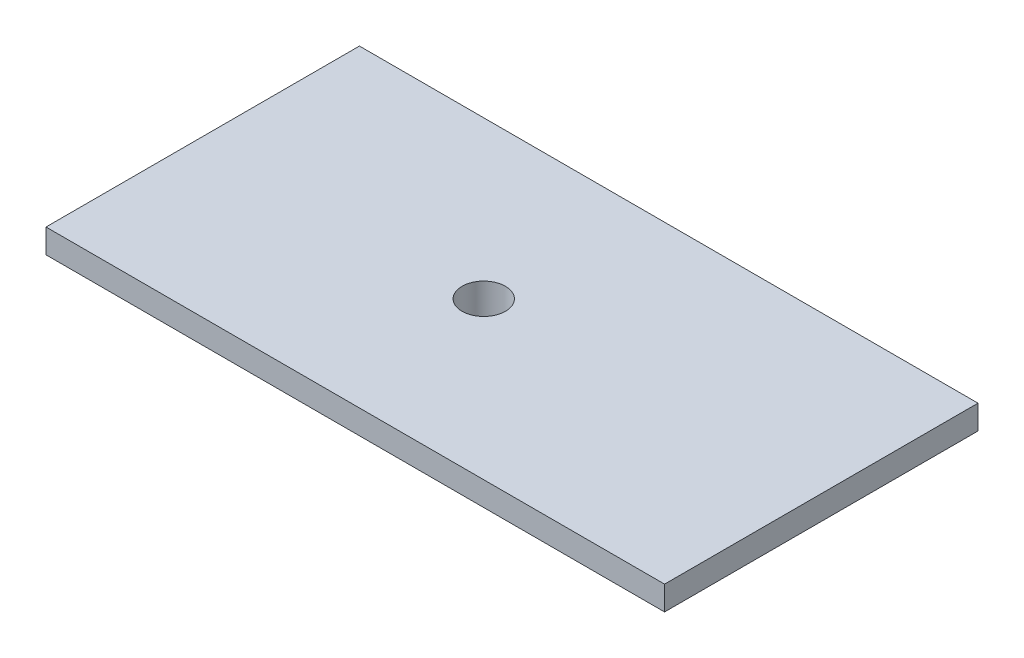
SolidWorks part; units mm, degrees
material "Pure Gold"
ref_plane "Front Plane" through (0, 0, 0) normal (0, 0, 1) x (1, 0, 0)
ref_plane "Top Plane" through (0, 0, 0) normal (0, 1, 0) x (1, 0, 0)
ref_plane "Right Plane" through (0, 0, 0) normal (1, 0, 0) x (0, 0, -1)
sketch "Sketch1" plane through (0, 0, 0) normal (0, 1, 0) x (1, 0, 0)
  line L1 (0, 0) -> (-128.28, 0)
  line L2 (0, 0) -> (0, 65)
  line L3 (0, 65) -> (-128.28, 65)
  line L4 (-128.28, 0) -> (-128.28, 65)
  dimension "D1" = 128.28
  dimension "D2" = 65
extrude "Boss-Extrude1" add sketch "Sketch1" along normal blind 5
sketch "Sketch3" plane through (0, 0, 0) normal (0, -1, 0) x (1, 0, 0)
  line L0 (-128.28, 0) -> (0, 0) construction
  line L1 (-123.18, -5.1) -> (-5.1, -5.1)
  line L2 (-123.18, -5.1) -> (-123.18, -59.9)
  line L3 (-123.18, -59.9) -> (-5.1, -59.9)
  line L4 (-5.1, -5.1) -> (-5.1, -59.9)
  line L5 (-128.28, -65) -> (-128.28, 0) construction
  line L6 (0, -65) -> (-128.28, -65) construction
  line L7 (0, 0) -> (0, -65) construction
  dimension "D1" = 5.1
  dimension "D2" = 5.1
  dimension "D3" = 5.1
  dimension "D4" = 5.1
extrude "Boss-Extrude2" add sketch "Sketch3" along normal blind 5
sketch "Sketch4" plane through (0, 5, 0) normal (0, 1, 0) x (1, 0, 0)
  line L0 (0, 0) -> (0, 65) construction
  line L1 (-128.28, 0) -> (0, 0) construction
  circle A0 centre (-70, 32.5) radius 4.5
  dimension "D1" = 70
  dimension "D3" = 9
  dimension "D2" = 32.5
extrude "Cut-Extrude1" cut sketch "Sketch4" against normal up to next
